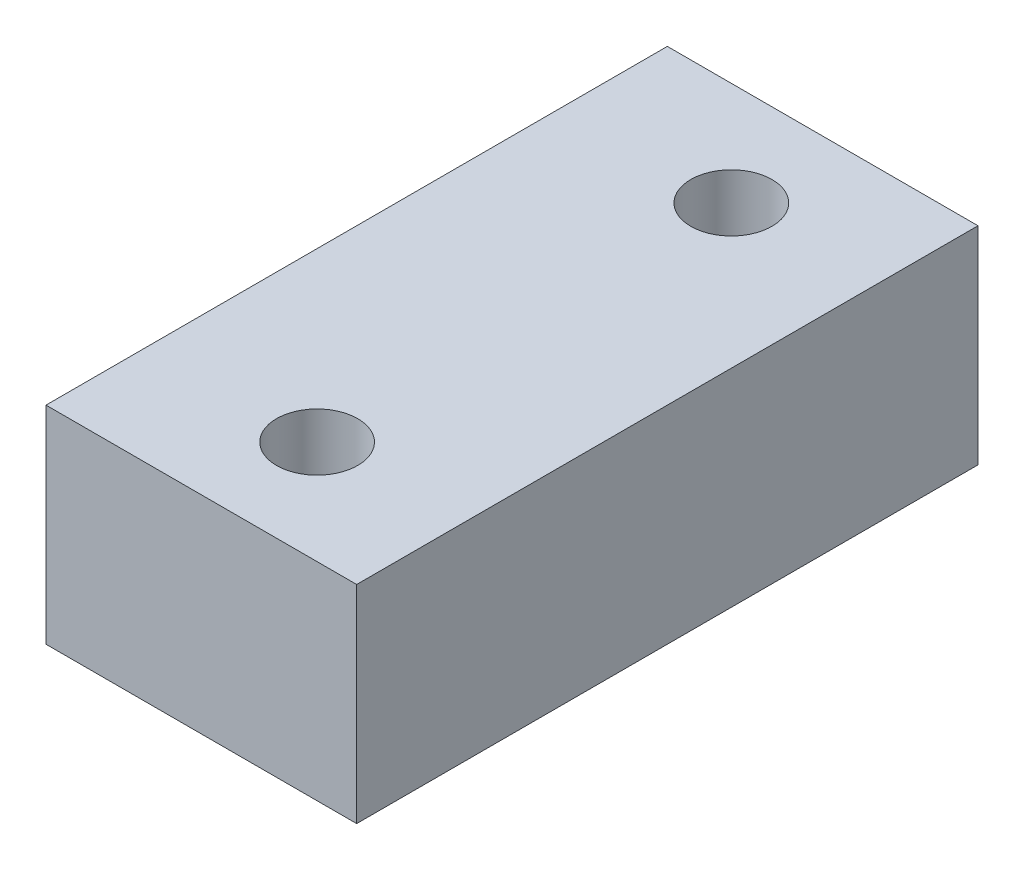
SolidWorks part; units mm, degrees
ref_plane "Front Plane" through (0, 0, 0) normal (0, 0, 1) x (1, 0, 0)
ref_plane "Top Plane" through (0, 0, 0) normal (0, 1, 0) x (1, 0, 0)
ref_plane "Right Plane" through (0, 0, 0) normal (1, 0, 0) x (0, 0, -1)
sketch "Sketch4" plane through (0, 0, 0) normal (0, 1, 0) x (1, 0, 0)
  line L8 (-61.3338, 18.9329) -> (-61.3338, -6.4671) construction
  line L9 (-61.3338, 6.2329) -> (-71.6088, 6.2329) construction
  line L10 (-71.6088, -0.9671) -> (-71.6088, 13.4329) construction
  line L11 (-71.6088, 6.2329) -> (-71.6088, 25.2829)
  line L12 (-71.6088, 25.2829) -> (-52.5588, 25.2829)
  line L13 (-52.5588, 25.2829) -> (-52.5588, -12.8171)
  line L14 (-52.5588, -12.8171) -> (-71.6088, -12.8171)
  line L15 (-71.6088, -12.8171) -> (-71.6088, 6.2329)
extrude "Boss-Extrude1" add sketch "Sketch4" along normal blind 12.7
sketch "Sketch5" plane through (0, 12.7, 0) normal (0, 1, 0) x (1, 0, 0)
  line L3 (-61.3338, 18.9329) -> (-61.3338, -6.4671) construction
hole_wizard "#10 Clearance Hole1" positions "Sketch6" profile "Sketch7" hole size "#10" standard "ANSI Inch" end condition through all
sketch "Sketch6" plane through (0, 12.7, 0) normal (0, 1, 0) x (1, 0, 0)
  point P0 (-61.3338, 18.9329)
  point P3 (-61.3338, -6.4671)
sketch "Sketch7" plane through (-61.3338, 12.7, -18.9329) normal (1, 0, 0) x (0, 0, 1)
  line L0 (0, 0) -> (0, 12.7)
  line L1 (0, 12.7) -> (2.4892, 12.7)
  line L2 (2.4892, 12.7) -> (2.4892, 0)
  line L5 (2.4892, 0) -> (0, 0)
  line L11 (0, -6.35) -> (0, 107.95) construction
  dimension "Thru Hole Dia." = 4.9784
  dimension "Thru Hole Depth" = 12.7
